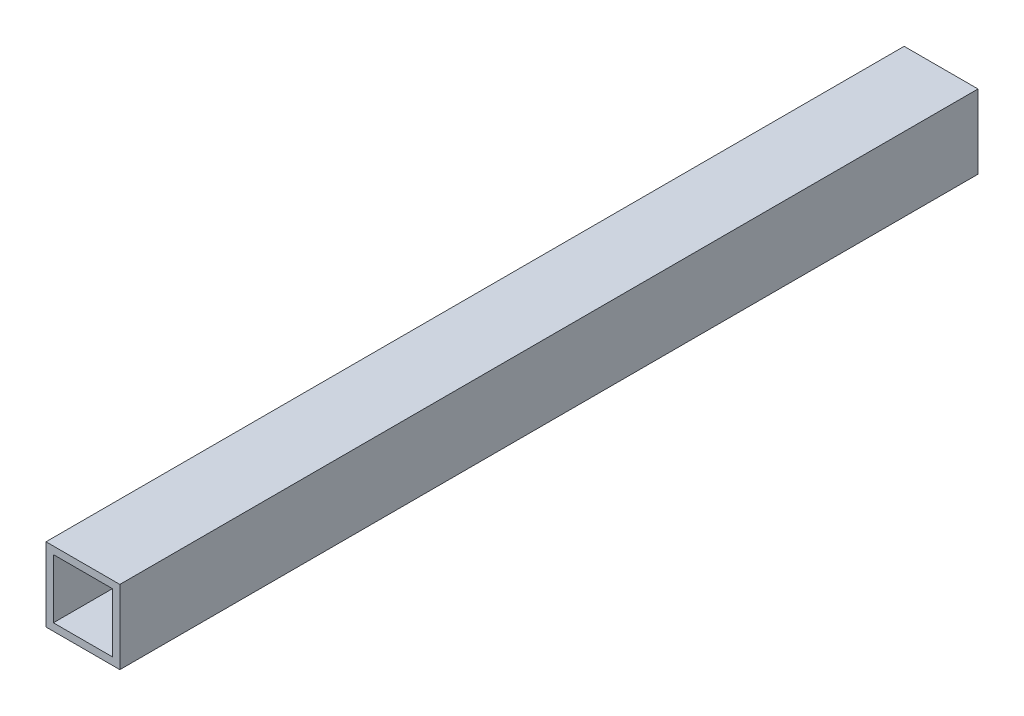
SolidWorks part; units mm, degrees
ref_plane "Front Plane" through (0, 0, 0) normal (0, 0, 1) x (1, 0, 0)
ref_plane "Top Plane" through (0, 0, 0) normal (0, 1, 0) x (1, 0, 0)
ref_plane "Right Plane" through (0, 0, 0) normal (1, 0, 0) x (0, 0, -1)
sketch "Sketch1" plane through (0, 0, 0) normal (0, 0, 1) x (1, 0, 0)
  line L1 (0, 20) -> (20, 20)
  line L2 (0, 20) -> (0, 0)
  line L3 (0, 0) -> (20, 0)
  line L4 (20, 20) -> (20, 0)
  dimension "D1" = 20
extrude "Extrude-Thin1" add sketch "Sketch1" along normal blind 232.4 thin
